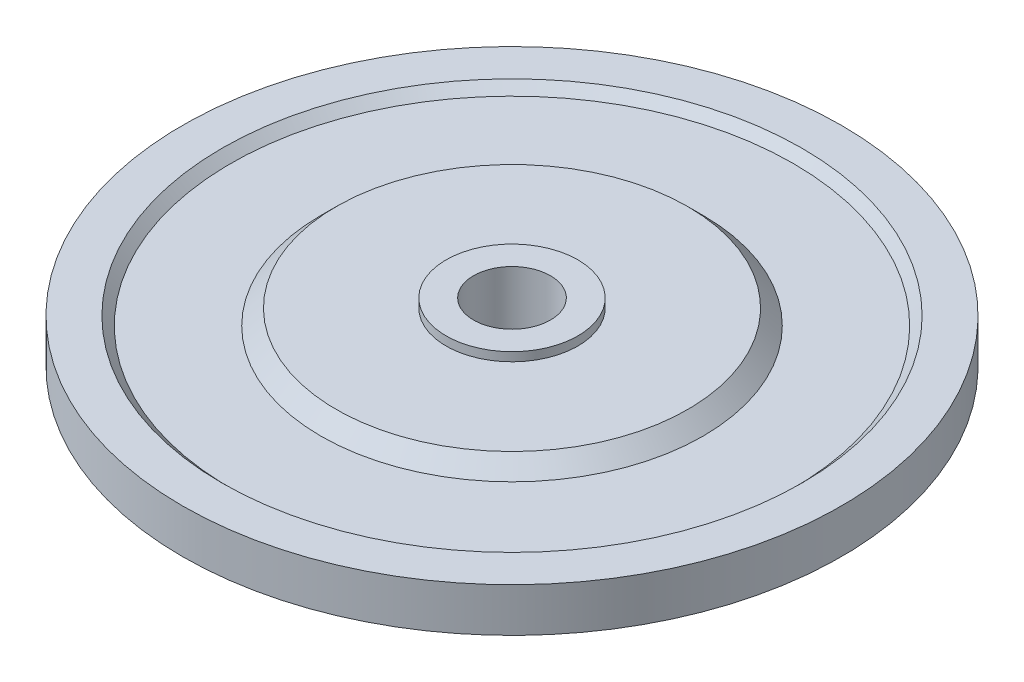
SolidWorks part; units mm, degrees
ref_plane "前视基准面" through (0, 0, 0) normal (0, 0, 1) x (1, 0, 0)
ref_plane "上视基准面" through (0, 0, 0) normal (0, 1, 0) x (1, 0, 0)
ref_plane "右视基准面" through (0, 0, 0) normal (1, 0, 0) x (0, 0, -1)
sketch "草图1" plane through (0, 0, 0) normal (0, 0, 1) x (1, 0, 0)
  line L0 (-17.5, 0) -> (-17.5, 34)
  line L1 (-17.5, 34) -> (-30, 34)
  line L2 (-30, 34) -> (-30, 30)
  line L3 (-30, 30) -> (-80, 30)
  line L4 (-80, 30) -> (-87, 23)
  line L5 (-87, 23) -> (-128, 23)
  line L6 (-128, 23) -> (-132, 27)
  line L7 (-132, 27) -> (-150, 27)
  line L8 (-150, 27) -> (-150, 7)
  line L9 (-150, 7) -> (-132, 7)
  line L10 (-132, 7) -> (-128, 11)
  line L11 (-128, 11) -> (-32.5, 11)
  line L12 (-32.5, 11) -> (-32.5, 0)
  line L13 (-32.5, 0) -> (-17.5, 0)
  line L14 (0, 0) -> (0, 26.3739) construction
  point P17 (-30, 32)
  point P19 (-135.3587, 2.8731)
  point P20 (-131.5416, 2.2514)
  point P21 (0, 0)
  point P22 (-141, 7)
  point P23 (0, 0)
  point P24 (0, 0)
  point P25 (0, 0)
  point P26 (-128, 16.6303)
  point P27 (-122.9999, 17.7104)
  dimension "D1" = 35
  dimension "D2" = 60
  dimension "D3" = 160
  dimension "D4" = 256
  dimension "D5" = 300
  dimension "D6" = 34
  dimension "D7" = 4
  dimension "D8" = 4
  dimension "D9" = 4
  dimension "D10" = 45
  dimension "D11" = 45
  dimension "D12" = 65
  dimension "D13" = 7
  dimension "D14" = 20
  dimension "D15" = 45
revolve "旋转1" add sketch "草图1" angle 360 about L14
